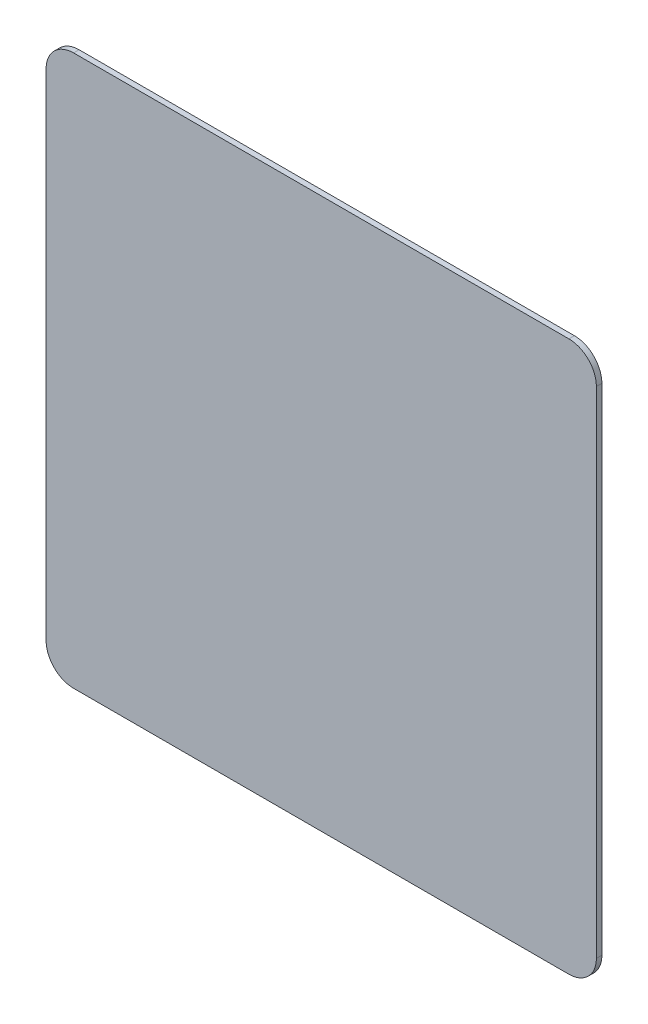
SolidWorks part; units mm, degrees
ref_plane "Front Plane" through (0, 0, 0) normal (0, 0, 1) x (1, 0, 0)
ref_plane "Top Plane" through (0, 0, 0) normal (0, 1, 0) x (1, 0, 0)
ref_plane "Right Plane" through (0, 0, 0) normal (1, 0, 0) x (0, 0, -1)
sketch "Sketch1" plane through (0, 0, 0) normal (0, 0, 1) x (1, 0, 0)
  line L1 (-90, -100) -> (90, -100)
  line L2 (-100, -90) -> (-100, 90)
  line L3 (-90, 100) -> (90, 100)
  line L4 (100, -90) -> (100, 90)
  line L5 (-100, -100) -> (100, 100) construction
  line L6 (-100, 100) -> (100, -100) construction
  arc A0 (-100, -90) -> (-90, -100) centre (-90, -90) ccw
  arc A1 (90, -100) -> (100, -90) centre (90, -90) ccw
  arc A2 (100, 90) -> (90, 100) centre (90, 90) ccw
  arc A3 (-90, 100) -> (-100, 90) centre (-90, 90) ccw
  point P0 (0, 0)
  dimension "D3" = 10
  dimension "D1" = 200
  dimension "D2" = 200
extrude "Boss-Extrude1" add sketch "Sketch1" along normal blind 2
